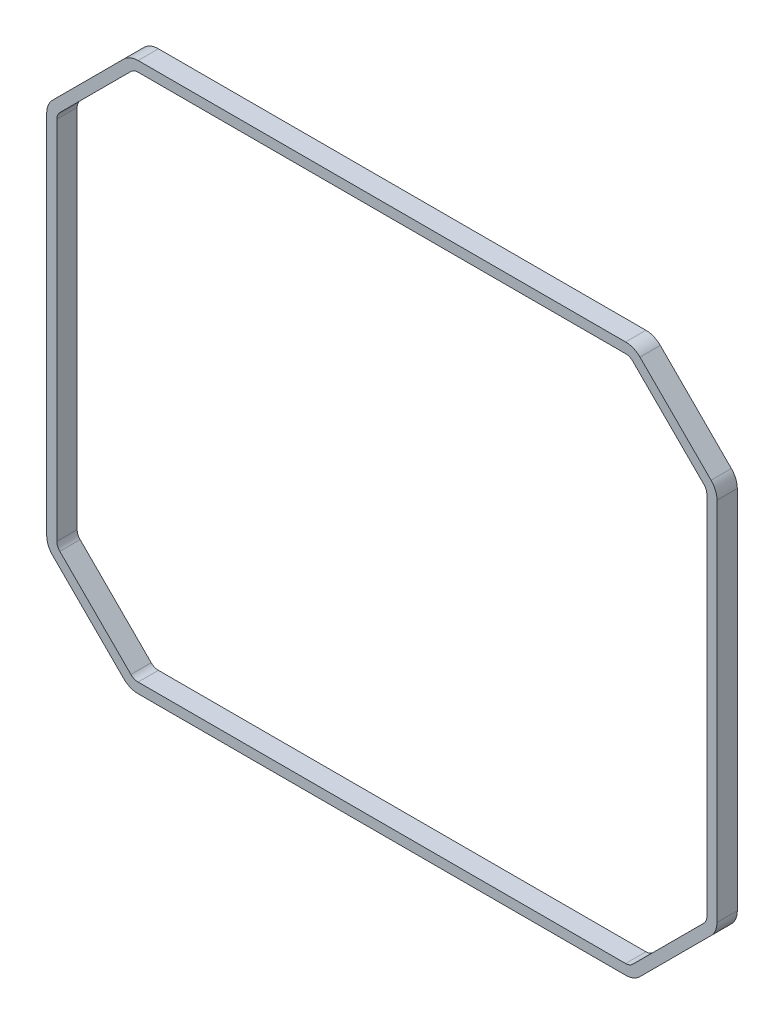
SolidWorks part; units mm, degrees
ref_plane "Plan de face" through (0, 0, 0) normal (0, 0, 1) x (1, 0, 0)
ref_plane "Plan de dessus" through (0, 0, 0) normal (0, 1, 0) x (1, 0, 0)
ref_plane "Plan de droite" through (0, 0, 0) normal (1, 0, 0) x (0, 0, -1)
sketch "Esquisse1" plane through (0, 0, 0) normal (0, 0, 1) x (1, 0, 0)
  line L8 (-24.0016, -27) -> (24.0016, -27)
  line L9 (32.4142, 19.4158) -> (25.4158, 26.4142)
  line L10 (33, -18.0016) -> (33, 18.0016)
  line L11 (25.4158, -26.4142) -> (32.4142, -19.4158)
  line L12 (24.0016, 27) -> (-24.0016, 27)
  line L13 (-33, 18.0016) -> (-33, -18.0016)
  line L14 (-32.4142, -19.4158) -> (-25.4158, -26.4142)
  line L15 (24.0016, 26) -> (-24.0016, 26)
  line L16 (0, 0) -> (0, 16.0449) construction
  line L17 (0, 0) -> (13.4471, 0) construction
  line L18 (-25.4158, 26.4142) -> (-32.4142, 19.4158)
  line L19 (-24.7087, 25.7071) -> (-31.7071, 18.7087)
  line L20 (-32, 18.0016) -> (-32, -18.0016)
  line L21 (-31.7071, -18.7087) -> (-24.7087, -25.7071)
  line L22 (-24.0016, -26) -> (24.0016, -26)
  line L23 (24.7087, -25.7071) -> (31.7071, -18.7087)
  line L24 (32, -18.0016) -> (32, 18.0016)
  line L25 (31.7071, 18.7087) -> (24.7087, 25.7071)
  arc A7 (-32.4142, -19.4158) -> (-33, -18.0016) centre (-31, -18.0016) cw
  arc A8 (-25.4158, -26.4142) -> (-24.0016, -27) centre (-24.0016, -25) ccw
  arc A9 (25.4158, -26.4142) -> (24.0016, -27) centre (24.0016, -25) cw
  arc A10 (32.4142, -19.4158) -> (33, -18.0016) centre (31, -18.0016) ccw
  arc A11 (32.4142, 19.4158) -> (33, 18.0016) centre (31, 18.0016) cw
  arc A12 (25.4158, 26.4142) -> (24.0016, 27) centre (24.0016, 25) ccw
  arc A13 (-32.4142, 19.4158) -> (-33, 18.0016) centre (-31, 18.0016) ccw
  arc A14 (-25.4158, 26.4142) -> (-24.0016, 27) centre (-24.0016, 25) cw
  arc A15 (-24.7087, 25.7071) -> (-24.0016, 26) centre (-24.0016, 25) cw
  arc A16 (-31.7071, 18.7087) -> (-32, 18.0016) centre (-31, 18.0016) ccw
  arc A17 (-31.7071, -18.7087) -> (-32, -18.0016) centre (-31, -18.0016) cw
  arc A18 (-24.7087, -25.7071) -> (-24.0016, -26) centre (-24.0016, -25) ccw
  arc A19 (24.7087, -25.7071) -> (24.0016, -26) centre (24.0016, -25) cw
  arc A20 (31.7071, -18.7087) -> (32, -18.0016) centre (31, -18.0016) ccw
  arc A21 (31.7071, 18.7087) -> (32, 18.0016) centre (31, 18.0016) cw
  arc A22 (24.7087, 25.7071) -> (24.0016, 26) centre (24.0016, 25) ccw
  point P6 (33, 27)
  point P8 (33, -27)
  point P9 (-24.5072, 27.3212)
  point P10 (-33.2079, 18.6205)
  point P12 (-33, -27)
  point P13 (-33, -18.83)
  point P21 (-33, 27)
  point P22 (-24.83, -27)
  point P25 (24.83, -27)
  point P28 (33, -18.83)
  point P31 (33, 18.83)
  point P34 (24.83, 27)
  point P37 (-33, 18.83)
  point P41 (-24.83, 27)
  point P66 (0, 0)
  dimension "D3" = 2
  dimension "D1" = 66
  dimension "D2" = 54
  dimension "D4" = 1
extrude "Boss.-Extru.1" add sketch "Esquisse1" along normal blind 2
